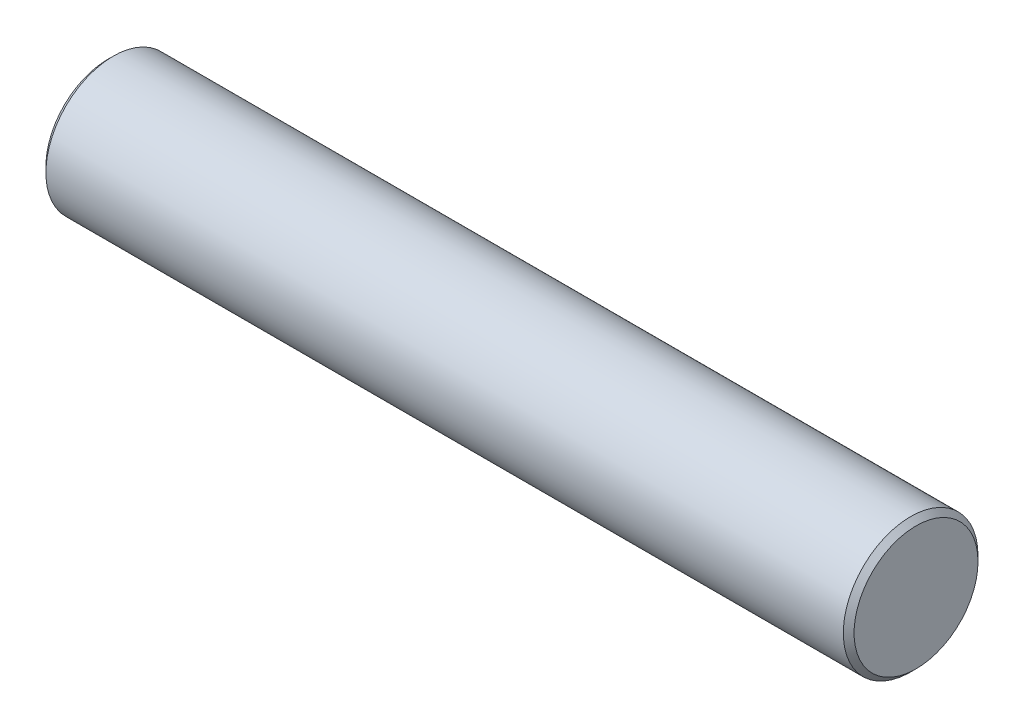
SolidWorks part; units mm, degrees
ref_plane "Front Plane" through (0, 0, 0) normal (0, 0, 1) x (1, 0, 0)
ref_plane "Top Plane" through (0, 0, 0) normal (0, 1, 0) x (1, 0, 0)
ref_plane "Right Plane" through (0, 0, 0) normal (1, 0, 0) x (0, 0, -1)
sketch "Sketch2" plane through (0, 0, 0) normal (0, 0, 1) x (1, 0, 0)
  line L1 (0, 0) -> (-30, 0)
  line L2 (0, 0) -> (0, 2.5)
  line L3 (0, 2.5) -> (-30, 2.5)
  line L4 (-30, 0) -> (-30, 2.5)
  dimension "D1" = 30
  dimension "D2" = 2.5
revolve "Revolve1" add sketch "Sketch2" angle 360 about L1
chamfer "Chamfer2" distance 0.2 angle 45 2 edges at (-30, 0, -2.5) (0, 0, -2.5)
ref_plane "Plane1" through (-15, 0, 0) normal (1, 0, 0) x (0, 0, -1)
